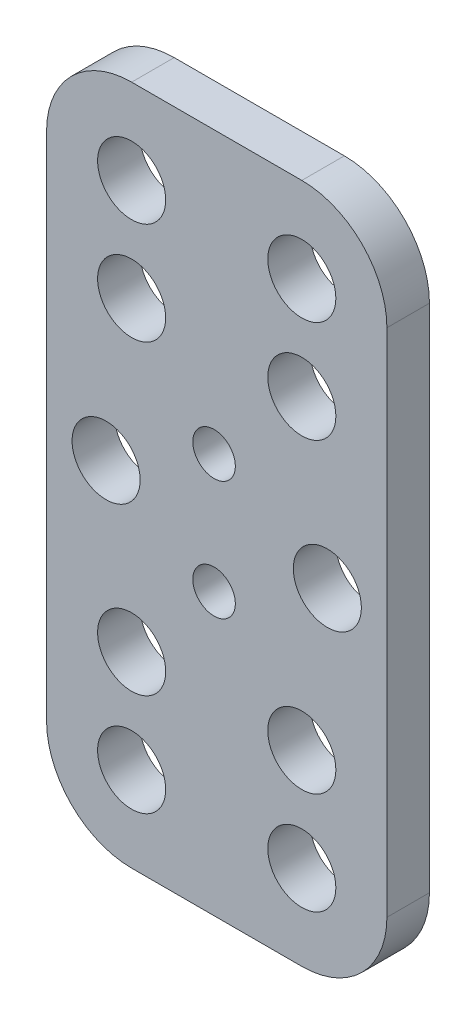
SolidWorks part; units mm, degrees
ref_plane "Front Plane" through (0, 0, 0) normal (0, 0, 1) x (1, 0, 0)
ref_plane "Top Plane" through (0, 0, 0) normal (0, 1, 0) x (1, 0, 0)
ref_plane "Right Plane" through (0, 0, 0) normal (1, 0, 0) x (0, 0, -1)
sketch "Sketch1" plane through (0, 0, 0) normal (0, 0, 1) x (1, 0, 0)
  line L1 (-9.6885, 40) -> (10.3115, 40)
  line L2 (-19.6885, 30) -> (-19.6885, -30)
  line L3 (-9.6885, -40) -> (10.3115, -40)
  line L4 (20.3115, 30) -> (20.3115, -30)
  circle A0 centre (0, 7) radius 2.5
  circle A1 centre (0, -7) radius 2.5
  circle A2 centre (-9.6885, 30) radius 4
  circle A3 centre (10.3115, 30) radius 4
  circle A4 centre (-9.6885, -30) radius 4
  circle A5 centre (10.3115, -30) radius 4
  circle A6 centre (-12.6885, 0) radius 4
  circle A7 centre (13.3115, 0) radius 4
  arc A8 (10.3115, -40) -> (20.3115, -30) centre (10.3115, -30) ccw
  arc A9 (-19.6885, -30) -> (-9.6885, -40) centre (-9.6885, -30) ccw
  arc A10 (10.3115, 40) -> (20.3115, 30) centre (10.3115, 30) cw
  arc A11 (-9.6885, 40) -> (-19.6885, 30) centre (-9.6885, 30) ccw
  circle A12 centre (-9.6885, -18) radius 4
  circle A13 centre (10.3115, -18) radius 4
  circle A14 centre (10.3115, 18) radius 4
  circle A15 centre (-9.6885, 18) radius 4
  point P0 (0, 0)
  point P25 (20.3115, -40)
  point P28 (-19.6885, -40)
  point P33 (-19.6885, 40)
  dimension "D3" = 7
  dimension "D5" = 10
  dimension "D12" = 10
  dimension "D13" = 12
  dimension "D11" = 5
  dimension "D16" = 5
  dimension "D1" = 80
  dimension "D2" = 40
  dimension "D4" = 7
  dimension "D6" = 10
  dimension "D7" = 10
  dimension "D8" = 10
  dimension "D9" = 7
  dimension "D10" = 7
  dimension "D14" = 12
  dimension "D15" = 12
extrude "Boss-Extrude1" add sketch "Sketch1" along normal blind 5
